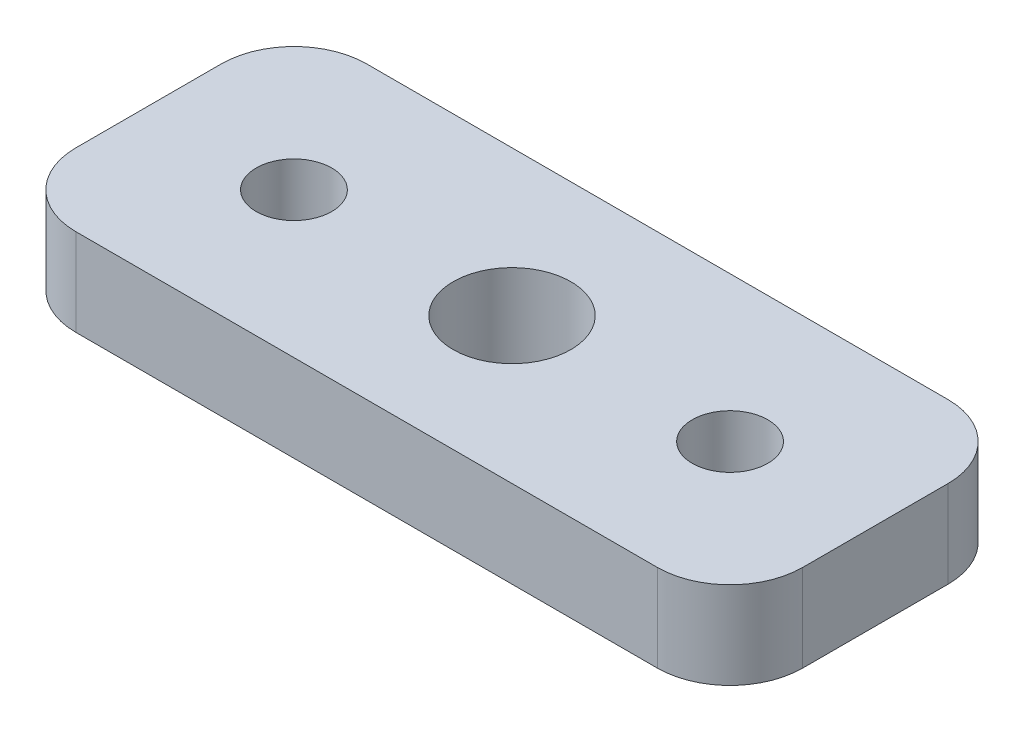
SolidWorks part; units mm, degrees
material "Acrílico (médio-alto impacto)"
ref_plane "Plano frontal" through (0, 0, 0) normal (0, 0, 1) x (1, 0, 0)
ref_plane "Plano superior" through (0, 0, 0) normal (0, 1, 0) x (1, 0, 0)
ref_plane "Plano direito" through (0, 0, 0) normal (1, 0, 0) x (0, 0, -1)
sketch "Esboço1" plane through (0, 0, 0) normal (0, 1, 0) x (1, 0, 0)
  line L1 (-25, 10) -> (25, 10)
  line L2 (-25, 10) -> (-25, -10)
  line L3 (-25, -10) -> (25, -10)
  line L4 (25, 10) -> (25, -10)
  line L5 (-25, 10) -> (25, -10) construction
  line L6 (-25, -10) -> (25, 10) construction
  point P0 (0, 0)
  dimension "D1" = 50
  dimension "D2" = 20
extrude "Ressalto-extrusão1" add sketch "Esboço1" along normal mid plane 6
sketch "Esboço3" plane through (0, 3, 0) normal (0, 1, 0) x (1, 0, 0)
  line L0 (-25, 0) -> (25, 0) construction
  line L1 (-25, 10) -> (-25, -10) construction
  line L2 (25, -10) -> (25, 10) construction
  line L3 (0, 10) -> (0, -10) construction
  line L4 (25, 10) -> (-25, 10) construction
  line L5 (-25, -10) -> (25, -10) construction
  circle A0 centre (0, 0) radius 4.05
  circle A1 centre (-15, 0) radius 2.6
  circle A2 centre (15, 0) radius 2.6
  dimension "D1" = 8.1
  dimension "D2" = 5.2
  dimension "D3" = 15
extrude "Corte-extrusão1" cut sketch "Esboço3" against normal blind 6
fillet "Filete1" radius 5 4 edges at (25, 0, 10) (-25, 0, -10) (25, 0, -10) (-25, 0, 10)
